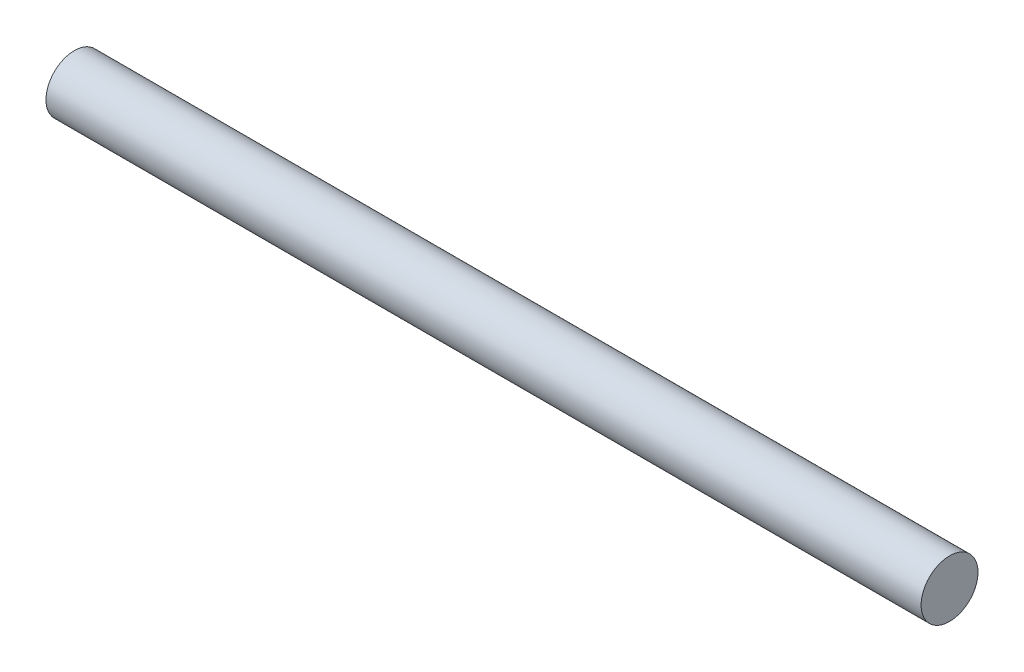
SolidWorks part; units mm, degrees
ref_plane "Front Plane" through (0, 0, 0) normal (0, 0, 1) x (1, 0, 0)
ref_plane "Top Plane" through (0, 0, 0) normal (0, 1, 0) x (1, 0, 0)
ref_plane "Right Plane" through (0, 0, 0) normal (1, 0, 0) x (0, 0, -1)
sketch "Sketch1" plane through (0, 0, 0) normal (1, 0, 0) x (0, 0, -1)
  circle A0 centre (0, 0) radius 6.5
  dimension "D1" = 13
extrude "Boss-Extrude1" add sketch "Sketch1" along normal blind 200
